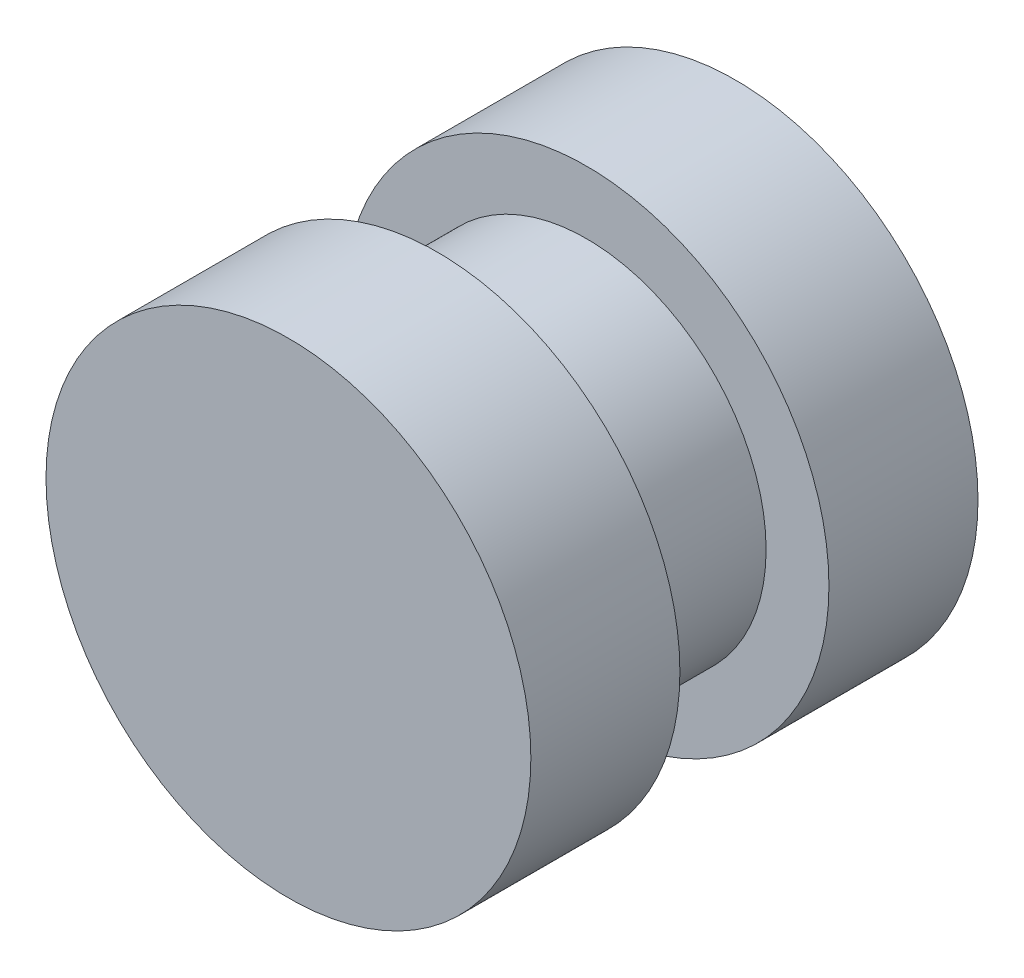
SolidWorks part; units mm, degrees
ref_plane "Front Plane" through (0, 0, 0) normal (0, 0, 1) x (1, 0, 0)
ref_plane "Top Plane" through (0, 0, 0) normal (0, 1, 0) x (1, 0, 0)
ref_plane "Right Plane" through (0, 0, 0) normal (1, 0, 0) x (0, 0, -1)
sketch "Sketch1" plane through (0, 0, 0) normal (0, 0, 1) x (1, 0, 0)
  circle A0 centre (0, 0) radius 10
  dimension "D1" = 20
extrude "Boss-Extrude1" add sketch "Sketch1" along normal blind 8.3
sketch "Sketch2" plane through (0, 0, 8.3) normal (0, 0, 1) x (1, 0, 0)
  circle A4 centre (0, 0) radius 13.5
  dimension "D1" = 27
extrude "Boss-Extrude4" add sketch "Sketch2" along normal blind 8.3
sketch "Sketch3" plane through (0, 0, 0) normal (0, 0, -1) x (-1, 0, 0)
  circle A0 centre (0, 0) radius 13.5
  dimension "D1" = 27
extrude "Boss-Extrude5" add sketch "Sketch3" along normal blind 8.3
